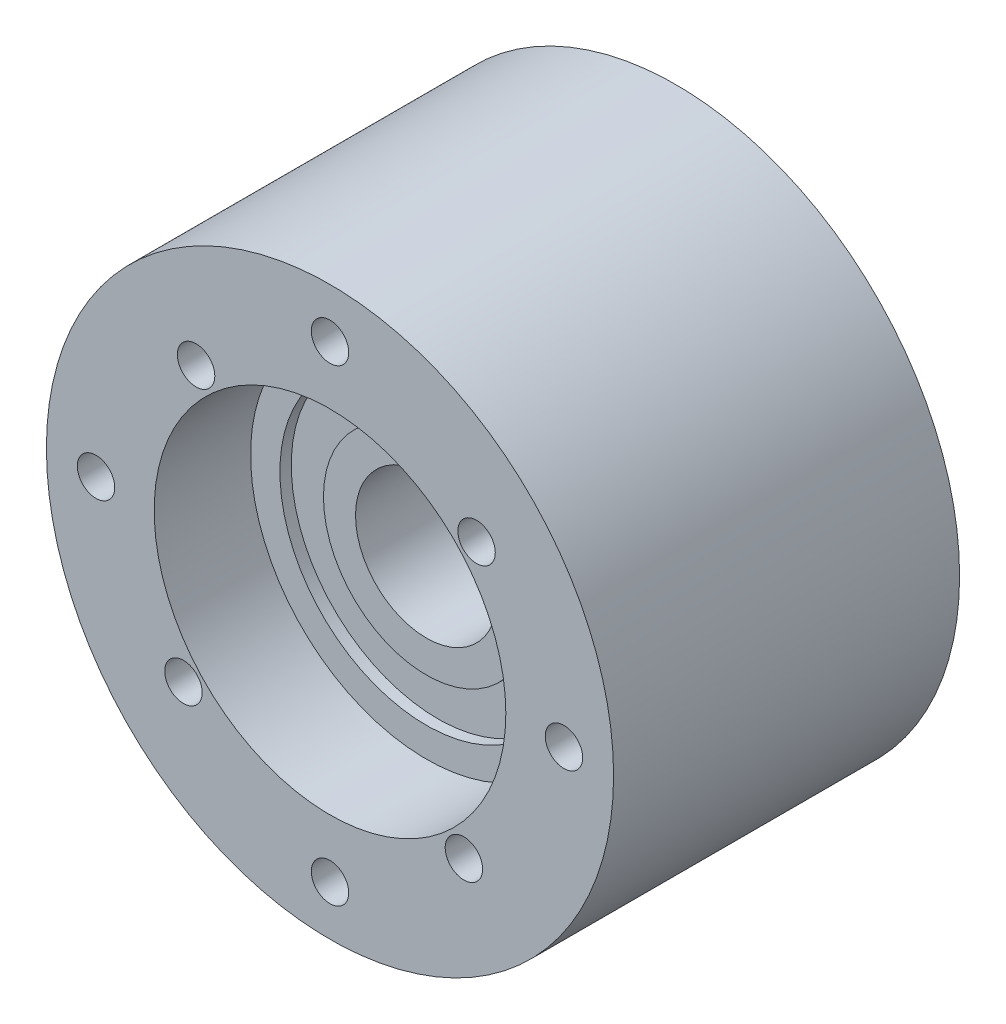
SolidWorks part; units mm, degrees
ref_plane "Plan de face" through (0, 0, 0) normal (0, 0, 1) x (1, 0, 0)
ref_plane "Plan de dessus" through (0, 0, 0) normal (0, 1, 0) x (1, 0, 0)
ref_plane "Plan de droite" through (0, 0, 0) normal (1, 0, 0) x (0, 0, -1)
sketch "Esquisse1" plane through (0, 0, 0) normal (0, 0, 1) x (1, 0, 0)
  circle A0 centre (0, 0) radius 50
  dimension "D1" = 100
extrude "Boss.-Extru.1" add sketch "Esquisse1" along normal blind 61
sketch "Esquisse2" plane through (0, 0, 0) normal (0, 0, -1) x (-1, 0, 0)
  circle A0 centre (0, 0) radius 32.5
  dimension "D1" = 65
extrude "Enlèv. mat.-Extru.1" cut sketch "Esquisse2" against normal blind 19
sketch "Esquisse3" plane through (0, 0, 19) normal (0, 0, -1) x (-1, 0, 0)
  circle A0 centre (0, 0) radius 30
  dimension "D1" = 60
extrude "Enlèv. mat.-Extru.2" cut sketch "Esquisse3" against normal blind 7
sketch "Esquisse5" plane through (0, 0, 26) normal (0, 0, -1) x (-1, 0, 0)
  circle A0 centre (0, 0) radius 12.5
  dimension "D1" = 25
extrude "Enlèv. mat.-Extru.3" cut sketch "Esquisse5" against normal through all
sketch "Esquisse8" plane through (0, 0, 0) normal (0, 0, -1) x (-1, 0, 0)
  circle A2 centre (0, 0) radius 41.25
  circle A3 centre (0, 0) radius 41.25 construction
  dimension "D1" = 8.75
hole_wizard "Chambrage pour vis à tête ronde bombée M61" positions "Esquisse12" profile "Esquisse11" counterbore size "M6" standard "Ansi Metric" end condition through all
sketch "Esquisse12" plane through (0, 0, 0) normal (0, 0, -1) x (-1, 0, 0)
  circle A0 centre (0, 0) radius 41.25 construction
  point P0 (41.25, 0)
  point P4 (0, 41.25)
  point P6 (-41.25, 0)
  point P8 (0, -41.25)
sketch "Esquisse11" plane through (-41.25, 0, 0) normal (1, 0, 0) x (0, 1, 0)
  line L0 (0, 0) -> (0, 61)
  line L1 (0, 61) -> (3.3, 61)
  line L3 (3.3, 61) -> (3.3, 4.6)
  line L4 (3.3, 4.6) -> (6.5, 4.6)
  line L5 (6.5, 4.6) -> (6.5, 0)
  line L7 (6.5, 0) -> (0, 0)
  line L11 (0, -6.35) -> (0, 107.95) construction
  dimension "Diamètre du perçage jusqu'au prochain" = 6.6
  dimension "Profondeur du perçage jusqu'au prochain" = 61
  dimension "Diamètre du chambrage" = 13
  dimension "Profondeur du chambrage" = 4.6
sketch "Esquisse13" plane through (0, 0, 61) normal (0, 0, 1) x (1, 0, 0)
  circle A0 centre (0, 0) radius 31
  dimension "D1" = 62
extrude "Enlèv. mat.-Extru.4" cut sketch "Esquisse13" against normal blind 17
sketch "Esquisse14" plane through (0, 0, 44) normal (0, 0, 1) x (1, 0, 0)
  circle A0 centre (0, 0) radius 18.1538
  circle A1 centre (0, 0) radius 25.8302
extrude "Enlèv. mat.-Extru.5" cut sketch "Esquisse14" against normal blind 2
hole_wizard "Dégagement M61" positions "Esquisse18" profile "Esquisse19" hole size "M6" standard "JIS"
sketch "Esquisse18" plane through (0, 0, 61) normal (0, 0, 1) x (1, 0, 0)
  point P0 (-23.6086, 25.8386)
  point P2 (-25.8386, -23.6086)
  point P4 (23.6086, -25.8386)
  point P6 (25.8386, 23.6086)
sketch "Esquisse19" plane through (-23.6086, 25.8386, 61) normal (1, 0, 0) x (0, -1, 0)
  line L0 (0, 0) -> (0, 6.9053)
  line L1 (0, 6.9053) -> (3.3, 5)
  line L2 (3.3, 5) -> (3.3, 0)
  line L5 (3.3, 0) -> (0, 0)
  line L10 (0, 6.9053) -> (-3.3, 5) construction
  line L11 (0, -6.35) -> (0, 107.95) construction
  dimension "Diamètre du perçage" = 6.6
  dimension "Profondeur du perçage" = 5
  dimension "Angle de pointe" = 120
